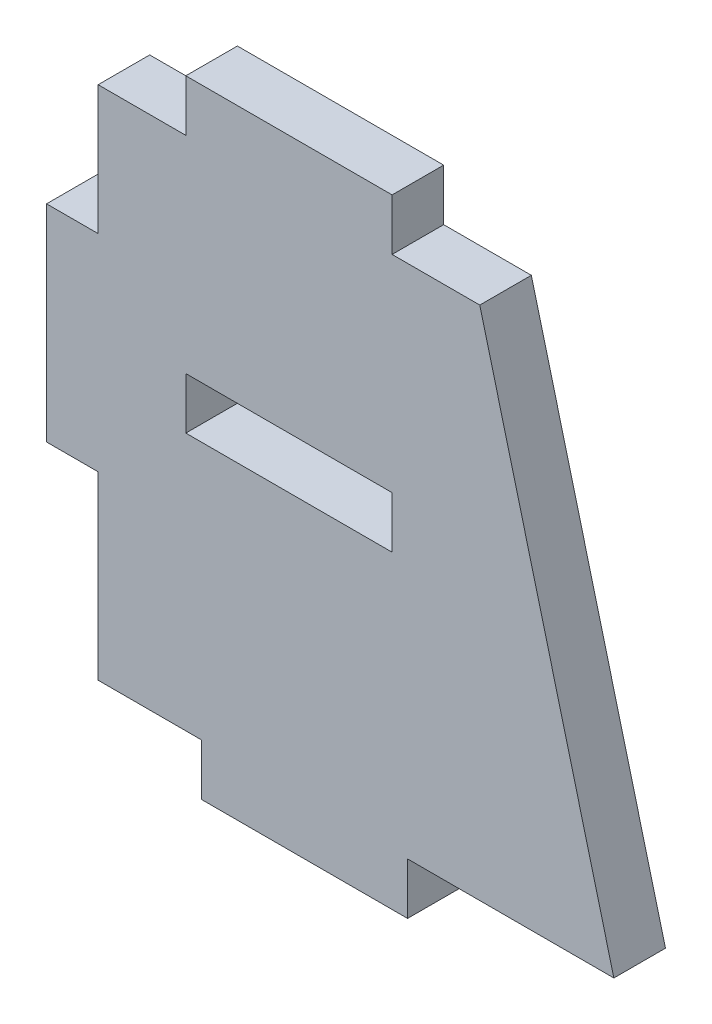
SolidWorks part; units mm, degrees
ref_plane "Front Plane" through (0, 0, 0) normal (0, 0, 1) x (1, 0, 0)
ref_plane "Top Plane" through (0, 0, 0) normal (0, 1, 0) x (1, 0, 0)
ref_plane "Right Plane" through (0, 0, 0) normal (1, 0, 0) x (0, 0, -1)
sketch "Sketch1" plane through (0, 0, 0) normal (0, 0, 1) x (1, 0, 0)
  line L0 (6.35, 28.575) -> (0, 28.575)
  line L1 (0, 28.575) -> (0, 53.975)
  line L2 (0, 53.975) -> (6.35, 53.975)
  line L3 (6.35, 28.575) -> (6.35, 6.35)
  line L4 (0, 28.575) -> (0, 0) construction
  line L5 (0, 0) -> (19.05, 0) construction
  line L6 (29.845, 69.85) -> (29.845, 6.35) construction
  line L7 (19.05, 6.35) -> (44.45, 6.35) construction
  line L8 (6.35, 69.85) -> (17.145, 69.85)
  line L9 (6.35, 6.35) -> (19.05, 6.35)
  line L10 (69.85, 6.35) -> (53.34, 69.85)
  line L11 (19.05, 6.35) -> (19.05, 0)
  line L12 (19.05, 0) -> (44.45, 0)
  line L13 (44.45, 0) -> (44.45, 6.35)
  line L14 (44.45, 6.35) -> (69.85, 6.35)
  line L15 (17.145, 69.85) -> (17.145, 76.2)
  line L16 (17.145, 44.45) -> (42.545, 44.45)
  line L17 (6.35, 69.85) -> (6.35, 53.975)
  line L18 (17.145, 44.45) -> (17.145, 38.1)
  line L19 (17.145, 38.1) -> (42.545, 38.1)
  line L20 (42.545, 44.45) -> (42.545, 38.1)
  line L21 (17.145, 76.2) -> (42.545, 76.2)
  line L22 (42.545, 76.2) -> (42.545, 69.85)
  line L23 (42.545, 69.85) -> (53.34, 69.85)
  line L24 (17.145, 69.85) -> (42.545, 69.85) construction
  point P18 (29.845, 44.45)
  dimension "D2" = 6.35
  dimension "D3" = 47.625
  dimension "D4" = 25.4
  dimension "D5" = 6.35
  dimension "D6" = 12.7
  dimension "D7" = 25.4
  dimension "D8" = 25.4
  dimension "D9" = 46.99
  dimension "D10" = 63.5
  dimension "D11" = 63.5
  dimension "D12" = 6.35
  dimension "D13" = 38.1
  dimension "D14" = 23.495
  dimension "D15" = 6.35
extrude "Extrude1" add sketch "Sketch1" along normal blind 6.35
